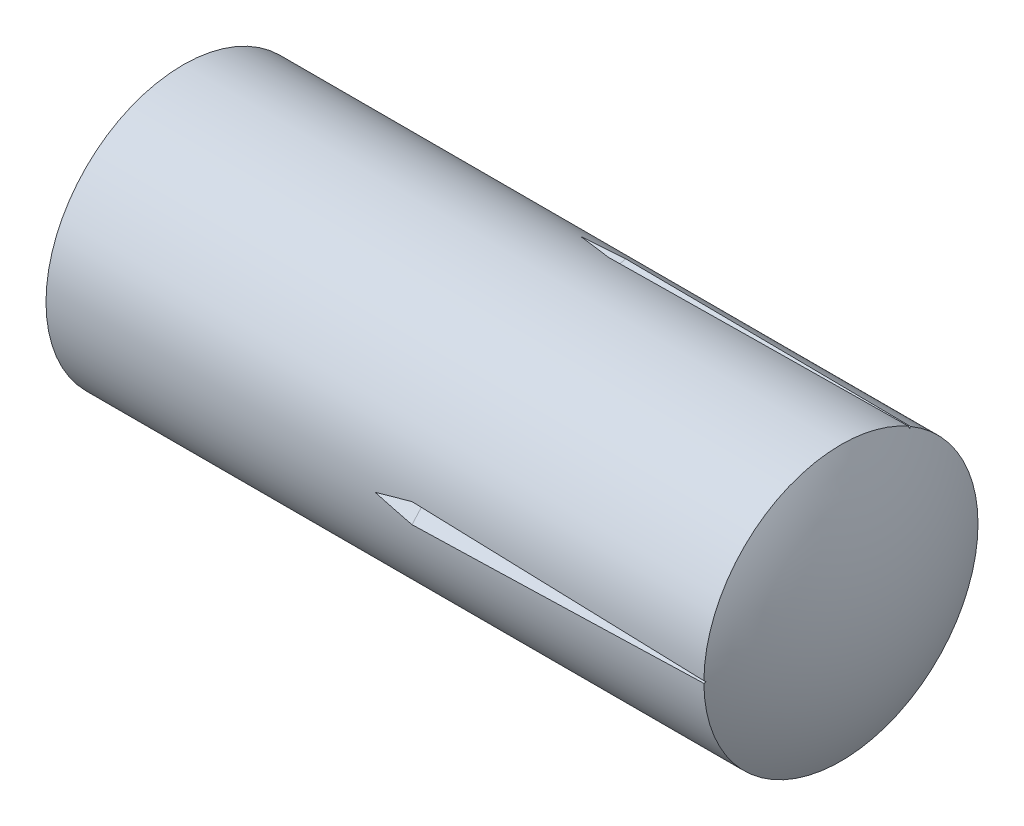
SolidWorks part; units mm, degrees
ref_plane "Plane1" through (0, 0, 0) normal (0, 0, 1) x (1, 0, 0)
ref_plane "Plane2" through (0, 0, 0) normal (0, 1, 0) x (1, 0, 0)
ref_plane "Plane3" through (0, 0, 0) normal (1, 0, 0) x (0, 0, -1)
other "Configuration Table"
sketch "Sketch1" plane through (0, 0, 0) normal (0, 0, 1) x (1, 0, 0)
  line L0 (-57, 0) -> (60, 0) construction
  line L1 (-4, 0) -> (-4, 0.15)
  line L2 (-3.6018, 1.5) -> (3.5981, 1.5)
  line L3 (-4, 0) -> (4, 0)
  arc A0 (-3.6018, 1.5) -> (-4, 0.15) centre (-1.0038, 0) ccw
  arc A1 (4, 0) -> (3.5981, 1.5) centre (1, 0) ccw
  dimension "D1" = 3
  dimension "D2" = 3
  dimension "Diameter" = 3
  dimension "Length" = 8
  dimension "D3" = 0.3
revolve "Base-Revolve" add sketch "Sketch1" angle 360 about L0
sketch "Sketch2" plane through (0, 0, 0) normal (1, 0, 0) x (0, 0, -1)
  line L0 (0, 0) -> (-14, 0) construction
  line L1 (-1.5, 0) -> (-3.3784, 1.3152)
  line L2 (-1.5, 0) -> (-3.3784, -1.3152)
  line L3 (-3.3784, -1.3152) -> (-3.3784, 1.3152)
  circle A0 centre (0, 0) radius 1.5 construction
  dimension "D1" = 3
  dimension "D2" = 70
  dimension "D3" = 35
  dimension "D4" = 1.8784
sketch "Sketch3" plane through (0, 0, 0) normal (0, 1, 0) x (1, 0, 0)
  line L0 (0, 0) -> (4, 0) construction
  line L1 (-57, 0) -> (60, 0) construction
  line L2 (0, -1.5) -> (0.375, -1.35)
  line L3 (0.375, -1.35) -> (4, -1.5)
  dimension "D2" = 3
  dimension "D1" = 4
  dimension "D3" = 2.7
  dimension "D4" = 3
  dimension "D5" = 0.375
sweep "Cut-Sweep1" cut profiles "Sketch2" path "Sketch3"
pattern_circular "CirPattern1" count 3 over 360 about axis through (0, 0, 0) along (1, 0, 0) of "Cut-Sweep1"
equation "\"D1@Sketch1\" = \"Diameter@Sketch1\""
equation "\"D2@Sketch1\" = \"Diameter@Sketch1\""
equation "\"D3@Sketch1\" = \"Diameter@Sketch1\" * .1"
equation "\"D1@Sketch2\" = \"Diameter@Sketch1\""
equation "\"D3@Sketch2\" = \"D2@Sketch2\" / 2"
equation "\"D1@Sketch3\" = \"Length@Sketch1\" / 2"
equation "\"D2@Sketch3\" = \"Diameter@Sketch1\""
equation "\"D3@Sketch3\" = \"Diameter@Sketch1\" * .9"
equation "\"D4@Sketch3\" = \"Diameter@Sketch1\""
equation "\"D5@Sketch3\" = \"D1@Sketch1\" / 8"
